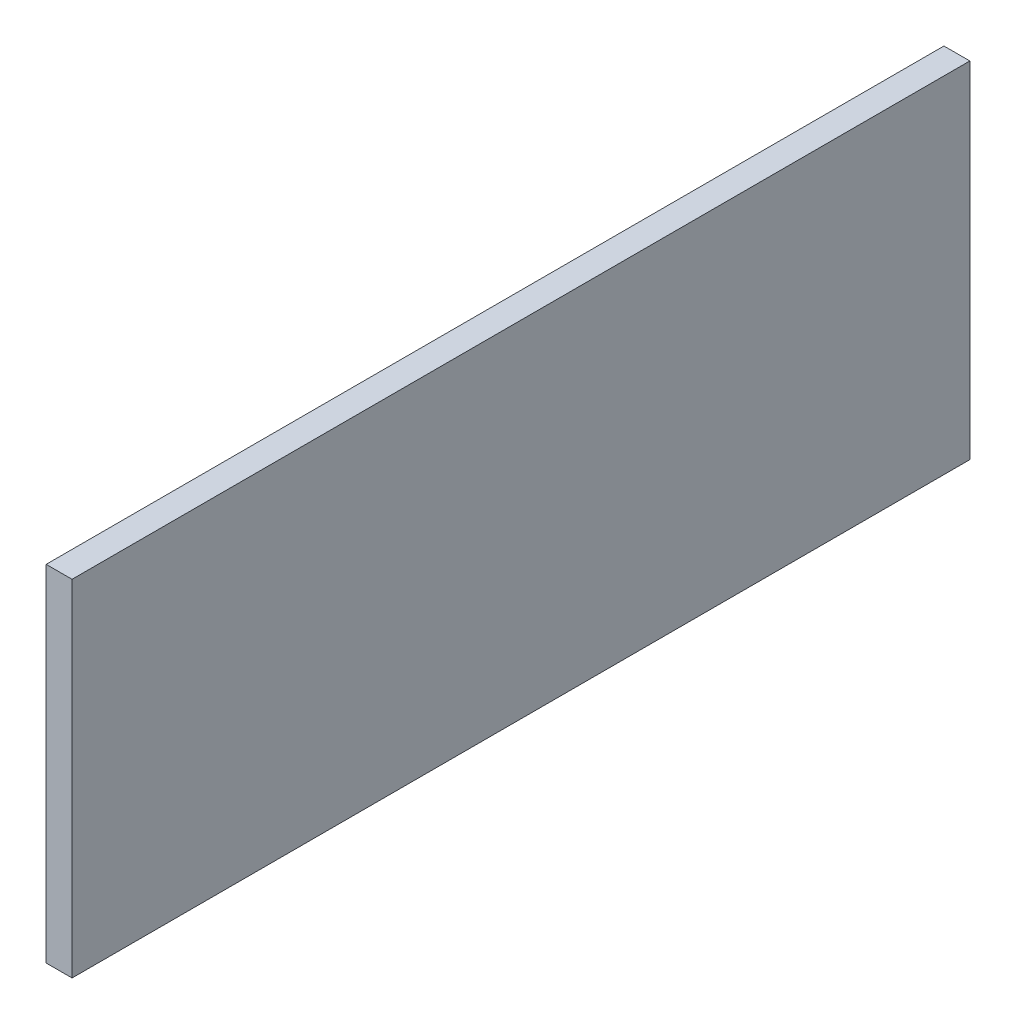
SolidWorks part; units mm, degrees
material "Maple"
ref_plane "Front Plane" through (0, 0, 0) normal (0, 0, 1) x (1, 0, 0)
ref_plane "Top Plane" through (0, 0, 0) normal (0, 1, 0) x (1, 0, 0)
ref_plane "Right Plane" through (0, 0, 0) normal (1, 0, 0) x (0, 0, -1)
sketch "Sketch1" plane through (0, 0, 0) normal (1, 0, 0) x (0, 0, -1)
  line L1 (-260, 0) -> (260, 0)
  line L2 (-260, 0) -> (-260, -200)
  line L3 (-260, -200) -> (260, -200)
  line L4 (260, 0) -> (260, -200)
  point P4 (0, 0)
  dimension "D1" = 520
  dimension "D2" = 200
extrude "Boss-Extrude1" add sketch "Sketch1" along normal blind 15
